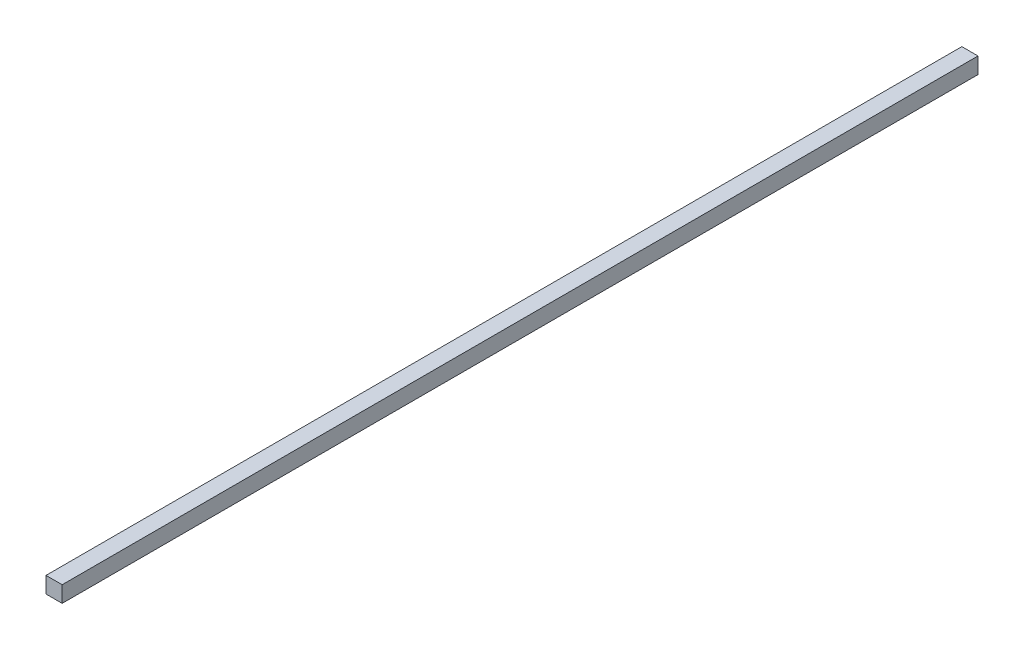
SolidWorks part; units mm, degrees
ref_plane "前视基准面" through (0, 0, 0) normal (0, 0, 1) x (1, 0, 0)
ref_plane "上视基准面" through (0, 0, 0) normal (0, 1, 0) x (1, 0, 0)
ref_plane "右视基准面" through (0, 0, 0) normal (1, 0, 0) x (0, 0, -1)
sketch "草图1" plane through (0, 0, 0) normal (0, 0, 1) x (1, 0, 0)
  line L1 (0, 0) -> (15, 0)
  line L2 (0, 0) -> (0, 15)
  line L3 (0, 15) -> (15, 15)
  line L4 (15, 0) -> (15, 15)
  dimension "D1" = 15
extrude "凸台-拉伸1" add sketch "草图1" along normal blind 850
